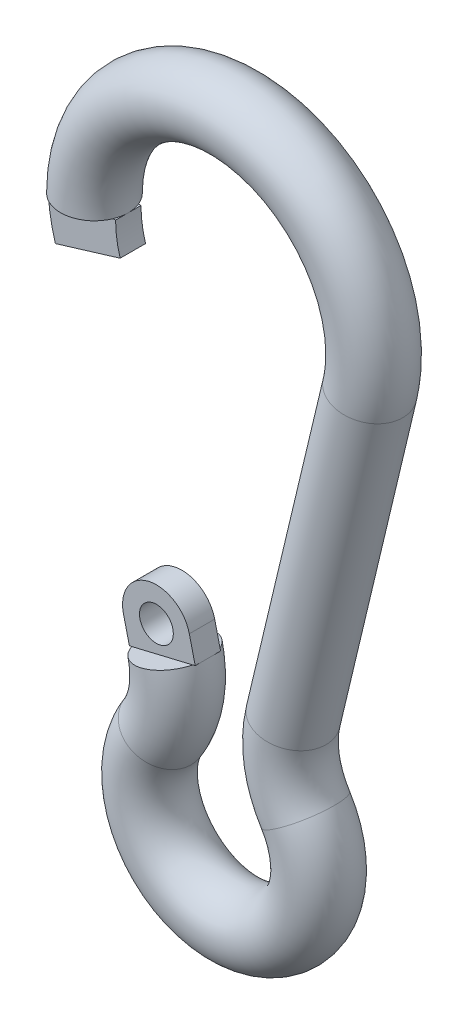
SolidWorks part; units mm, degrees
material "AISI 1020"
ref_plane "Front Plane" through (0, 0, 0) normal (0, 0, 1) x (1, 0, 0)
ref_plane "Top Plane" through (0, 0, 0) normal (0, 1, 0) x (1, 0, 0)
ref_plane "Right Plane" through (0, 0, 0) normal (1, 0, 0) x (0, 0, -1)
sketch "Sketch2" plane through (0, 0, 0) normal (0, 0, 1) x (1, 0, 0)
  line L0 (16.0492, -3.8304) -> (6.9801, -41.8304)
  arc A0 (-16.5, 0) -> (16.0492, -3.8304) centre (0, 0) cw
  arc A1 (6.9801, -41.8304) -> (8.4493, -50.6512) centre (18.1659, -44.5) ccw
  arc A2 (8.4493, -50.6512) -> (-8.4493, -50.6512) centre (0, -56) cw
  arc A3 (-8.4493, -50.6512) -> (-6.9801, -41.8304) centre (-18.1659, -44.5) ccw
  dimension "D1" = 16.5
  dimension "D2" = 10
  dimension "D3" = 11.5
  dimension "D4" = 44.5
  dimension "D5" = 11.5
sweep "Sweep1" add path "Sketch2" circular profile diameter 8 parameters "D3"=8
sketch "Sketch12" plane through (0, 0, 0) normal (0, 0, 1) x (1, 0, 0)
  line L0 (-19.6146, -5.9597) -> (-11.9601, -3.6339)
  line L1 (-3.0893, -40.9018) -> (-10.8708, -42.7589) construction
  line L2 (-3.0893, -40.9018) -> (-10.8708, -42.7589)
  line L3 (-10.8708, -42.7589) -> (-11.5672, -39.8409)
  line L4 (-3.7858, -37.9837) -> (-3.0893, -40.9018)
  line L6 (-20.5, 0) -> (-12.5, 0)
  arc A0 (-20.5, 0) -> (-19.6146, -5.9597) centre (0, 0) ccw
  arc A1 (19.94, -4.7589) -> (-20.5, 0) centre (0, 0) ccw construction
  arc A2 (-12.5, 0) -> (-11.9601, -3.6339) centre (0, 0) ccw
  arc A3 (12.1585, -2.9018) -> (-12.5, 0) centre (0, 0) ccw construction
  arc A4 (-11.5672, -39.8409) -> (-3.7858, -37.9837) centre (-7.6765, -38.9123) cw
  circle A5 centre (-7.6765, -38.9123) radius 2
  dimension "D1" = 4
  dimension "D2" = 3
  dimension "D4" = 8
extrude "Boss-Extrude1" add sketch "Sketch12" along normal mid plane 3
